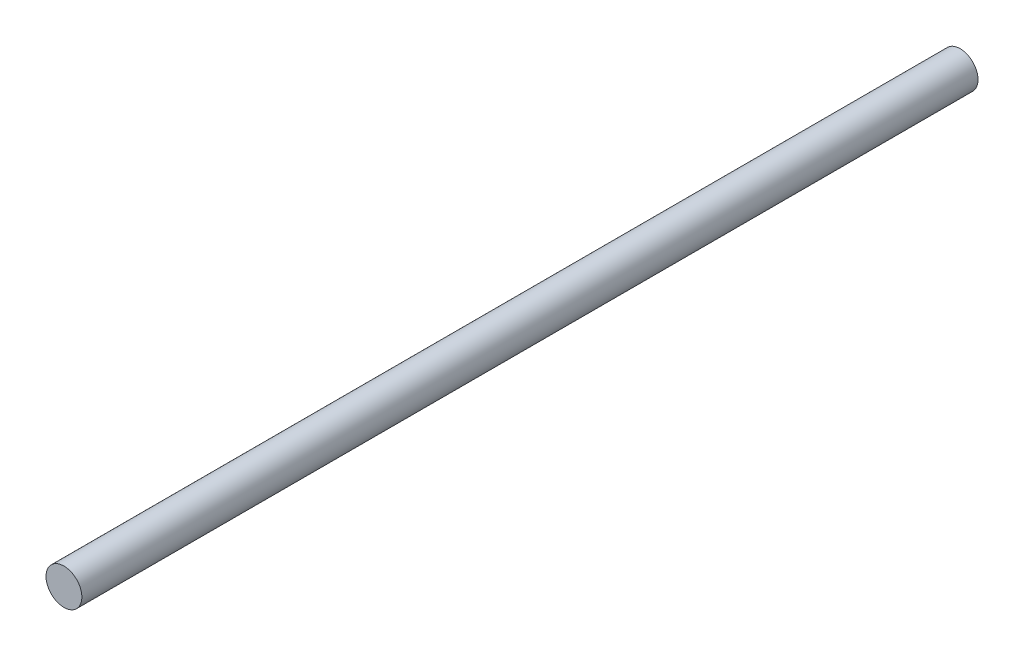
SolidWorks part; units mm, degrees
ref_plane "Front Plane" through (0, 0, 0) normal (0, 0, 1) x (1, 0, 0)
ref_plane "Top Plane" through (0, 0, 0) normal (0, 1, 0) x (1, 0, 0)
ref_plane "Right Plane" through (0, 0, 0) normal (1, 0, 0) x (0, 0, -1)
sketch "Sketch1" plane through (0, 0, 0) normal (0, 0, 1) x (1, 0, 0)
  circle A0 centre (0, 0) radius 6.35
  dimension "D1" = 12.7
extrude "Boss-Extrude1" add sketch "Sketch1" along normal blind 317.5
